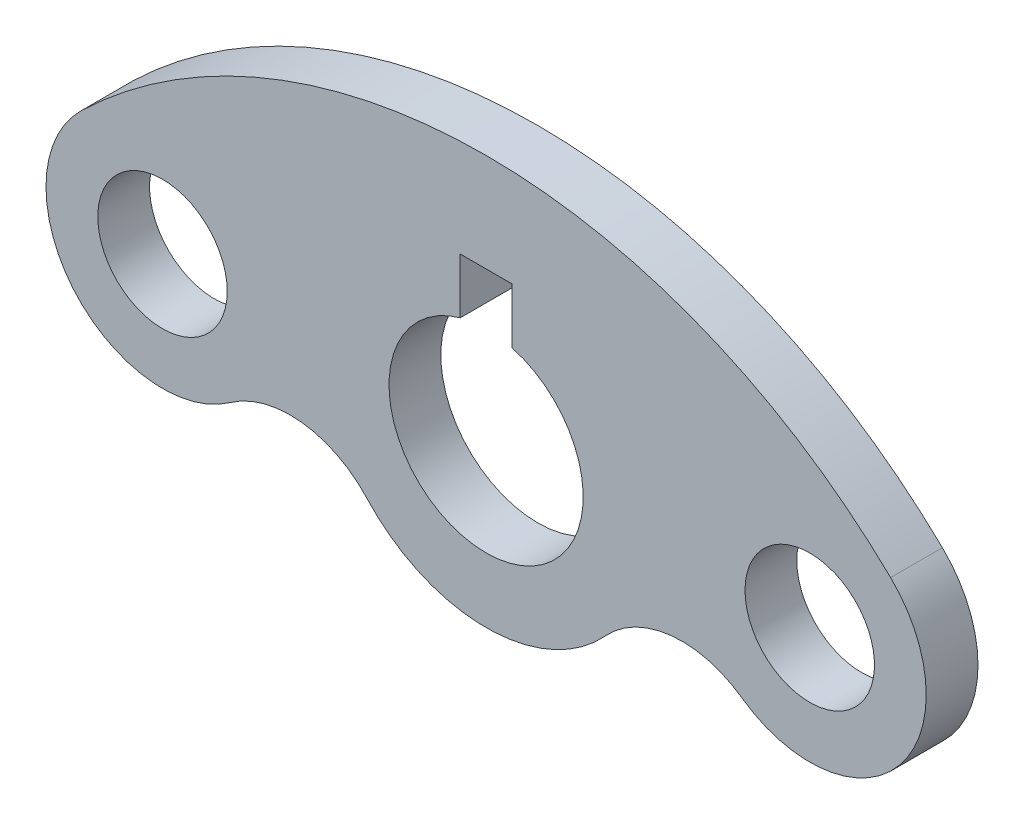
SolidWorks part; units mm, degrees
ref_plane "Alzado" through (0, 0, 0) normal (0, 0, 1) x (1, 0, 0)
ref_plane "Planta" through (0, 0, 0) normal (0, 1, 0) x (1, 0, 0)
ref_plane "Vista lateral" through (0, 0, 0) normal (1, 0, 0) x (0, 0, -1)
sketch "Croquis1" plane through (0, 0, 0) normal (0, 0, 1) x (1, 0, 0)
  line L0 (0, -51.8073) -> (0, 97.0848) construction
  line L1 (4, 14.4568) -> (4, 23)
  line L2 (4, 23) -> (-4, 23)
  line L3 (-4, 23) -> (-4, 14.4568)
  arc A0 (-50, 0) -> (50, 0) centre (0, 0) cw construction
  arc A1 (-62.5, 12.9518) -> (62.5, 12.9518) centre (0, -51.8073) cw
  arc A3 (39.5441, -14.6518) -> (62.5, 12.9518) centre (50, 0) ccw
  arc A4 (-62.5, 12.9518) -> (-39.5441, -14.6518) centre (-50, 0) ccw
  circle A5 centre (-50, 0) radius 10
  arc A6 (-18.4451, -16.8754) -> (-39.5441, -14.6518) centre (-30.25, -27.6756) ccw
  arc A7 (-4, 14.4568) -> (4, 14.4568) centre (0, 0) ccw
  arc A8 (-18.4451, -16.8754) -> (18.4451, -16.8754) centre (0, 0) ccw
  arc A9 (18.4451, -16.8754) -> (39.5441, -14.6518) centre (30.25, -27.6756) cw
  circle A11 centre (50, 0) radius 10
  point P3 (0, 72)
  point P6 (0, 0)
  point P13 (0, -53.7282)
  dimension "D1" = 90
  dimension "D2" = 18
  dimension "D3" = 20
  dimension "D4" = 30
  dimension "D5" = 50
  dimension "D6" = 32
  dimension "D7" = 100
  dimension "D8" = 23
  dimension "D9" = 8
extrude "Saliente-Extruir2" add sketch "Croquis1" along normal blind 8
